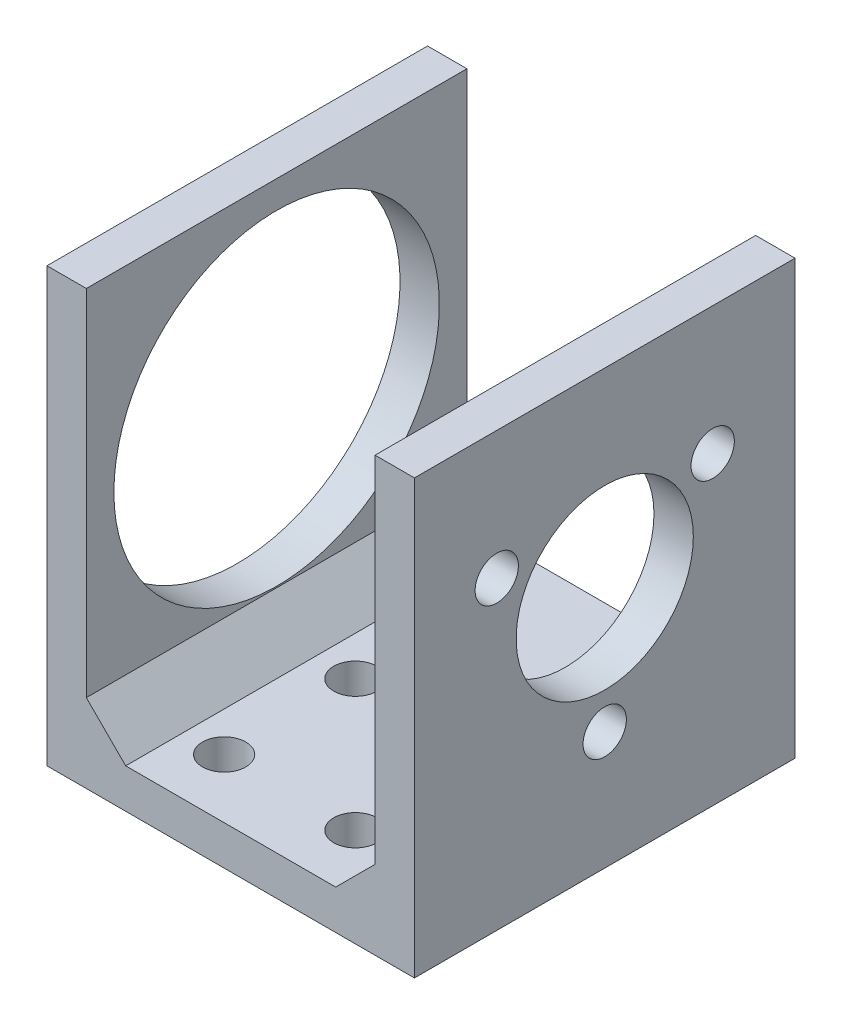
SolidWorks part; units mm, degrees
ref_plane "前视基准面" through (0, 0, 0) normal (0, 0, 1) x (1, 0, 0)
ref_plane "上视基准面" through (0, 0, 0) normal (0, 1, 0) x (1, 0, 0)
ref_plane "右视基准面" through (0, 0, 0) normal (1, 0, 0) x (0, 0, -1)
sketch "草图1" plane through (0, 0, 0) normal (0, 1, 0) x (1, 0, 0)
  line L1 (-14, -14.5) -> (14, -14.5)
  line L2 (-14, -14.5) -> (-14, 14.5)
  line L3 (-14, 14.5) -> (14, 14.5)
  line L4 (14, -14.5) -> (14, 14.5)
  line L5 (-14, -14.5) -> (14, 14.5) construction
  line L6 (-14, 14.5) -> (14, -14.5) construction
  point P0 (0, 0)
  dimension "D1" = 28
  dimension "D2" = 29
extrude "凸台-拉伸1" add sketch "草图1" along normal blind 3
sketch "草图2" plane through (0, 3, 0) normal (0, 1, 0) x (1, 0, 0)
  line L0 (-14, -14.5) -> (14, -14.5) construction
  line L1 (14, 14.5) -> (11, 14.5)
  line L2 (14, 14.5) -> (14, -14.5)
  line L3 (14, -14.5) -> (11, -14.5)
  line L4 (11, 14.5) -> (11, -14.5)
  line L5 (14, 14.5) -> (-14, 14.5) construction
  line L6 (-14, 14.5) -> (-11, 14.5)
  line L7 (-14, 14.5) -> (-14, -14.5)
  line L8 (-14, -14.5) -> (-11, -14.5)
  line L9 (-11, 14.5) -> (-11, -14.5)
  line L10 (-14, 14.5) -> (-14, -14.5) construction
  dimension "D1" = 3
  dimension "D2" = 3
extrude "凸台-拉伸2" add sketch "草图2" along normal blind 30
sketch "草图3" plane through (-14, 0, 0) normal (-1, 0, 0) x (0, 0, 1)
  line L0 (-14.5, 33) -> (-14.5, 0) construction
  line L1 (-14.5, 33) -> (14.5, 33) construction
  line L3 (-14.5, 18.5) -> (-14.5, 33)
  line L4 (-14.5, 33) -> (0, 33)
  line L5 (0, 33) -> (14.5, 33)
  line L6 (14.5, 33) -> (14.5, 18.5)
  line L7 (14.5, 18.5) -> (14.5, 33)
  line L8 (-14.5, 33) -> (-14.5, 18.5)
  line L9 (-14.5, 33) -> (-14.5, 18.5)
  line L10 (-14.5, 18.5) -> (-14.5, 33)
  arc A0 (14.5, 18.5) -> (-14.5, 18.5) centre (0, 18.5) ccw
  circle A1 centre (0, 18.5) radius 9.5
  circle A2 centre (-8.2272, 23.25) radius 1.65
  circle A3 centre (8.2272, 23.25) radius 1.65
  circle A4 centre (0, 9) radius 1.65
  point P23 (0, 18.5)
  dimension "D2" = 3.3
  dimension "D3" = 19
  dimension "D4" = 3
  dimension "D5" = 14.5
extrude "切除-拉伸1" cut sketch "草图3" against normal blind 33 contours A2 | A3 | A4
sketch "草图5" plane through (0, 0, -14.5) normal (0, 0, -1) x (-1, 0, 0)
  line L0 (11, 3) -> (11, 6)
  line L1 (11, 33) -> (11, 3) construction
  line L2 (11, 6) -> (8, 3)
  line L3 (-11, 3) -> (11, 3) construction
  line L4 (8, 3) -> (11, 3)
  line L5 (-11, 3) -> (-11, 6)
  line L6 (-11, 33) -> (-11, 3) construction
  line L7 (-11, 6) -> (-8, 3)
  line L8 (-8, 3) -> (-11, 3)
  dimension "D1" = 3
  dimension "D2" = 3
  dimension "D3" = 3
  dimension "D4" = 3
extrude "凸台-拉伸3" add sketch "草图5" against normal blind 29
sketch "草图6" plane through (-14, 0, 0) normal (-1, 0, 0) x (0, 0, 1)
  line L0 (14.5, 33) -> (14.5, 0) construction
  line L2 (-14.5, 33) -> (14.5, 33) construction
  circle A0 centre (0, 18.5) radius 12.4
  dimension "D1" = 24.8
  dimension "D2" = 14.5
  dimension "D3" = 14.5
extrude "切除-拉伸2" cut sketch "草图6" against normal blind 5 contours A0
sketch "草图8" plane through (0, 3, 0) normal (0, 1, 0) x (1, 0, 0)
  line L1 (-5, -10) -> (5, -10)
  line L2 (-5, -10) -> (-5, 10)
  line L3 (-5, 10) -> (5, 10)
  line L4 (5, -10) -> (5, 10)
  line L5 (-5, -10) -> (5, 10) construction
  line L6 (-5, 10) -> (5, -10) construction
  circle A0 centre (5, 10) radius 1.65
  circle A1 centre (5, -10) radius 1.65
  circle A2 centre (-5, -10) radius 1.65
  circle A3 centre (-5, 10) radius 1.65
  circle A4 centre (5, -10) radius 2.5
  circle A5 centre (5, 0) radius 1.65
  circle A6 centre (-5, 0) radius 1.65
  point P0 (0, 0)
  dimension "D3" = 3.3
  dimension "D4" = 5
  dimension "D5" = 3.3
  dimension "D6" = 3.3
  dimension "D1" = 20
  dimension "D2" = 10
extrude "切除-拉伸3" cut sketch "草图8" against normal blind 5 contours L3 A3 L2 | L2 A3 L3 | L4 A0 L3 | L3 A0 L4 | L1 A1 L4 | L4 A1 L1 | L2 A2 L1 | L1 A2 L2 | A5 | A6
sketch "草图9" plane through (14, 0, 0) normal (1, 0, 0) x (0, 0, -1)
  line L1 (-14.5, 33) -> (14.5, 33) construction
  line L2 (14.5, 33) -> (14.5, 0) construction
  circle A0 centre (0, 18.5) radius 6.75
  dimension "D1" = 13.5
  dimension "D2" = 14.5
  dimension "D3" = 14.5
extrude "切除-拉伸4" cut sketch "草图9" against normal blind 5
